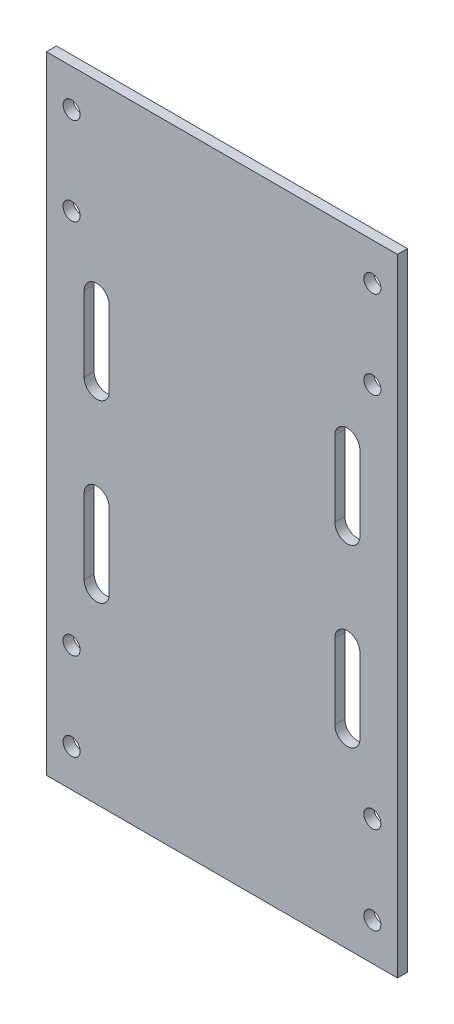
SolidWorks part; units mm, degrees
material "6061 Alloy"
ref_plane "Front Plane" through (0, 0, 0) normal (0, 0, 1) x (1, 0, 0)
ref_plane "Top Plane" through (0, 0, 0) normal (0, 1, 0) x (1, 0, 0)
ref_plane "Right Plane" through (0, 0, 0) normal (1, 0, 0) x (0, 0, -1)
sketch "Sketch1" plane through (0, 0, 0) normal (0, 0, 1) x (1, 0, 0)
  line L1 (-35, -62.5) -> (35, -62.5)
  line L2 (-35, -62.5) -> (-35, 62.5)
  line L3 (-35, 62.5) -> (35, 62.5)
  line L4 (35, -62.5) -> (35, 62.5)
  line L5 (-35, -62.5) -> (35, 62.5) construction
  line L6 (-35, 62.5) -> (35, -62.5) construction
  dimension "D1" = 35
  dimension "D2" = 35
  dimension "D3" = 62.5
  dimension "D4" = 62.5
extrude "Boss-Extrude1" add sketch "Sketch1" against normal blind 2
sketch "Sketch2" plane through (0, 0, 0) normal (0, 0, 1) x (1, 0, 0)
  circle A0 centre (-30, -55) radius 1.7
  circle A1 centre (-30, -37.5) radius 1.7
  circle A2 centre (-30, 37.5) radius 1.7
  circle A3 centre (-30, 55) radius 1.7
  circle A4 centre (30, -55) radius 1.7
  circle A5 centre (30, -37.5) radius 1.7
  circle A6 centre (30, 37.5) radius 1.7
  circle A7 centre (30, 55) radius 1.7
  dimension "D1" = 3.4
  dimension "D2" = 30
  dimension "D3" = 30
  dimension "D4" = 37.5
  dimension "D5" = 55
  dimension "D6" = 37.5
  dimension "D7" = 55
extrude "Lo_xuyen_M3_D3_4" cut sketch "Sketch2" along normal through all and the other way through all
sketch "Sketch3" plane through (0, 0, 0) normal (0, 0, 1) x (1, 0, 0)
  line L1 (-27.5, -25) -> (-22.5, -25)
  line L2 (-27.5, -25) -> (-27.5, -10)
  line L3 (-27.5, -10) -> (-22.5, -10)
  line L4 (-22.5, -25) -> (-22.5, -10)
  line L5 (-27.5, -25) -> (-22.5, -10) construction
  line L6 (-27.5, -10) -> (-22.5, -25) construction
  line L7 (-27.5, 10) -> (-22.5, 10)
  line L8 (-27.5, 10) -> (-27.5, 25)
  line L9 (-27.5, 25) -> (-22.5, 25)
  line L10 (-22.5, 10) -> (-22.5, 25)
  line L11 (-27.5, 10) -> (-22.5, 25) construction
  line L12 (-27.5, 25) -> (-22.5, 10) construction
  line L13 (22.5, -25) -> (27.5, -25)
  line L14 (22.5, -25) -> (22.5, -10)
  line L15 (22.5, -10) -> (27.5, -10)
  line L16 (27.5, -25) -> (27.5, -10)
  line L17 (22.5, -25) -> (27.5, -10) construction
  line L18 (22.5, -10) -> (27.5, -25) construction
  line L19 (22.5, 10) -> (27.5, 10)
  line L20 (22.5, 10) -> (22.5, 25)
  line L21 (22.5, 25) -> (27.5, 25)
  line L22 (27.5, 10) -> (27.5, 25)
  line L23 (22.5, 10) -> (27.5, 25) construction
  line L24 (22.5, 25) -> (27.5, 10) construction
  point P0 (-25, -17.5)
  point P5 (-25, 17.5)
  point P10 (25, -17.5)
  point P15 (25, 17.5)
  dimension "D1" = 22.5
  dimension "D2" = 25
  dimension "D3" = 22.5
  dimension "D4" = 10
  dimension "D5" = 17.5
  dimension "D6" = 10
extrude "Than_ranh" cut sketch "Sketch3" along normal through all and the other way through all
sketch "Sketch4" plane through (0, 0, 0) normal (0, 0, 1) x (1, 0, 0)
  line L0 (-27.5, -25) -> (-22.5, -25) construction
  line L1 (-22.5, -10) -> (-27.5, -10) construction
  line L2 (-27.5, 10) -> (-22.5, 10) construction
  line L3 (-22.5, 25) -> (-27.5, 25) construction
  line L4 (22.5, -25) -> (27.5, -25) construction
  line L5 (27.5, -10) -> (22.5, -10) construction
  line L6 (22.5, 10) -> (27.5, 10) construction
  line L7 (27.5, 25) -> (22.5, 25) construction
  circle A0 centre (-25, -25) radius 2.5
  circle A1 centre (-25, -10) radius 2.5
  circle A2 centre (-25, 10) radius 2.5
  circle A3 centre (-25, 25) radius 2.5
  circle A4 centre (25, -25) radius 2.5
  circle A5 centre (25, -10) radius 2.5
  circle A6 centre (25, 10) radius 2.5
  circle A7 centre (25, 25) radius 2.5
extrude "Dau_ranh_R2_5" cut sketch "Sketch4" along normal through all and the other way through all
